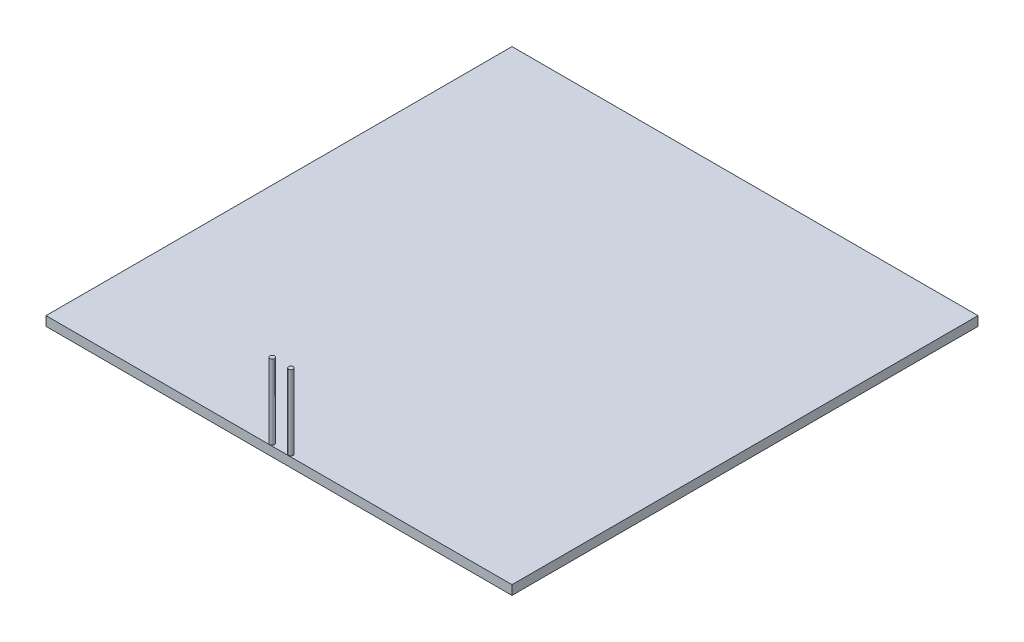
SolidWorks part; units mm, degrees
ref_plane "Front Plane" through (0, 0, 0) normal (0, 0, 1) x (1, 0, 0)
ref_plane "Top Plane" through (0, 0, 0) normal (0, 1, 0) x (1, 0, 0)
ref_plane "Right Plane" through (0, 0, 0) normal (1, 0, 0) x (0, 0, -1)
sketch "Sketch2" plane through (0, 0, 0) normal (0, 1, 0) x (1, 0, 0)
  line L0 (0, -250) -> (0, -216.8375) construction
  line L1 (250, -250) -> (-250, -250)
  line L2 (250, -250) -> (250, 250)
  line L3 (250, 250) -> (-250, 250)
  line L4 (-250, -250) -> (-250, 250)
  line L5 (250, -250) -> (-250, 250) construction
  line L6 (250, 250) -> (-250, -250) construction
  point P0 (0, 0)
  dimension "D1" = 500
  dimension "D2" = 500
extrude "Boss-Extrude1" add sketch "Sketch2" along normal blind 10
sketch "Sketch5" plane through (0, 10, 0) normal (0, 1, 0) x (1, 0, 0)
  line L0 (0, -250) -> (0, -138.8239) construction
  circle A0 centre (-9.9998, -247.2632) radius 2.475
  circle A1 centre (10, -247.1684) radius 2.475
  dimension "D1" = 4.95
  dimension "D2" = 4.95
  dimension "D3" = 20
  dimension "D4" = 10
extrude "Boss-Extrude2" add sketch "Sketch5" along normal blind 80
